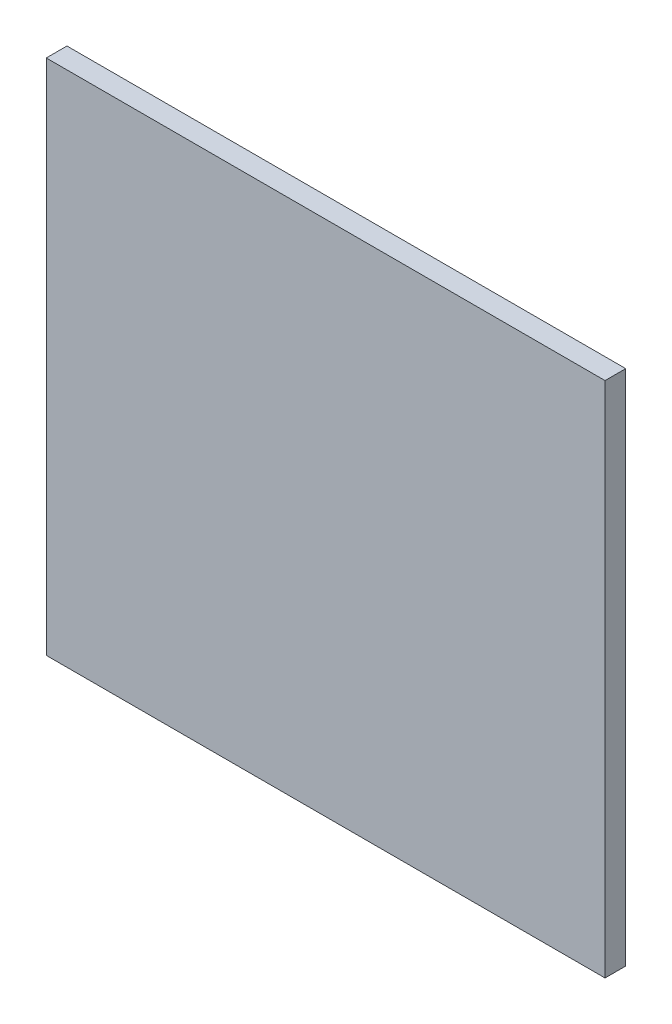
SolidWorks part; units mm, degrees
material "1023 Carbon Steel Sheet (SS)"
ref_plane "Front Plane" through (0, 0, 0) normal (0, 0, 1) x (1, 0, 0)
ref_plane "Top Plane" through (0, 0, 0) normal (0, 1, 0) x (1, 0, 0)
ref_plane "Right Plane" through (0, 0, 0) normal (1, 0, 0) x (0, 0, -1)
sketch "Sketch1" plane through (0, 0, 0) normal (0, 0, 1) x (1, 0, 0)
  line L1 (-67.5, -62.5) -> (67.5, -62.5)
  line L2 (-67.5, -62.5) -> (-67.5, 62.5)
  line L3 (-67.5, 62.5) -> (67.5, 62.5)
  line L4 (67.5, -62.5) -> (67.5, 62.5)
  line L5 (-67.5, -62.5) -> (67.5, 62.5) construction
  line L6 (-67.5, 62.5) -> (67.5, -62.5) construction
  point P0 (0, 0)
  dimension "D1" = 135
  dimension "D2" = 125
extrude "Boss-Extrude1" add sketch "Sketch1" along normal blind 5
